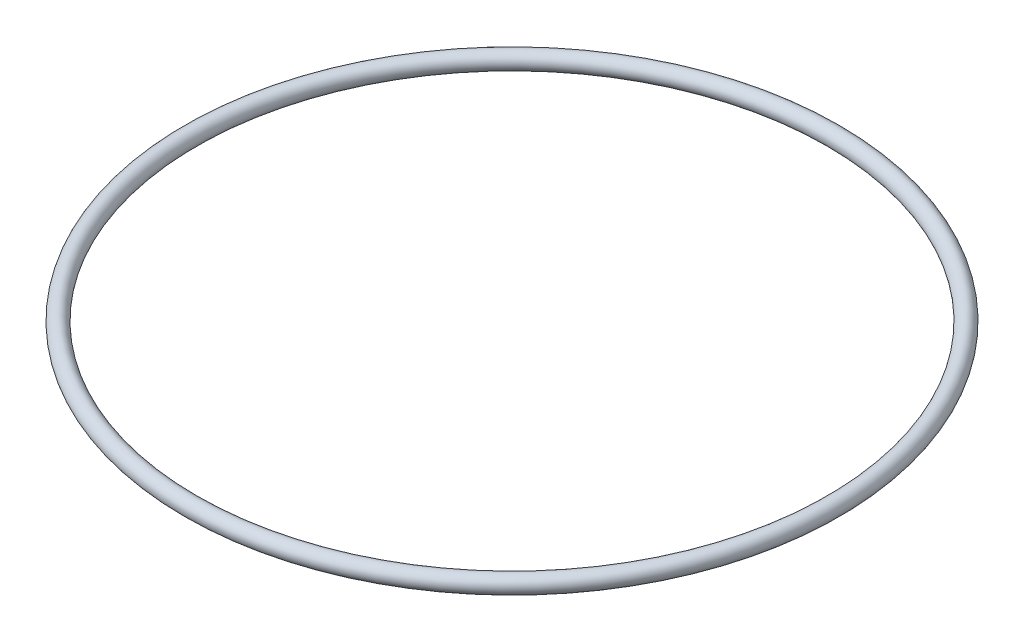
SolidWorks part; units mm, degrees
material "BUTYL"
ref_plane "Plano frontal" through (0, 0, 0) normal (0, 0, 1) x (1, 0, 0)
ref_plane "Plano superior" through (0, 0, 0) normal (0, 1, 0) x (1, 0, 0)
ref_plane "Plano direito" through (0, 0, 0) normal (1, 0, 0) x (0, 0, -1)
sketch "Esboço1" plane through (0, 0, 0) normal (0, 0, 1) x (1, 0, 0)
  line L0 (0, -33.2907) -> (0, 36.7177) construction
  circle A0 centre (-66.65, 0) radius 1.765
  point P5 (-64.885, 0)
  dimension "D1" = 3.53
  dimension "D2" = 64.885
revolve "Revolução1" add sketch "Esboço1" angle 360 about L0
sketch "Esboço2" plane through (0, 0, 0) normal (0, 1, 0) x (1, 0, 0)
  circle A0 centre (0, 0) radius 52.4425
